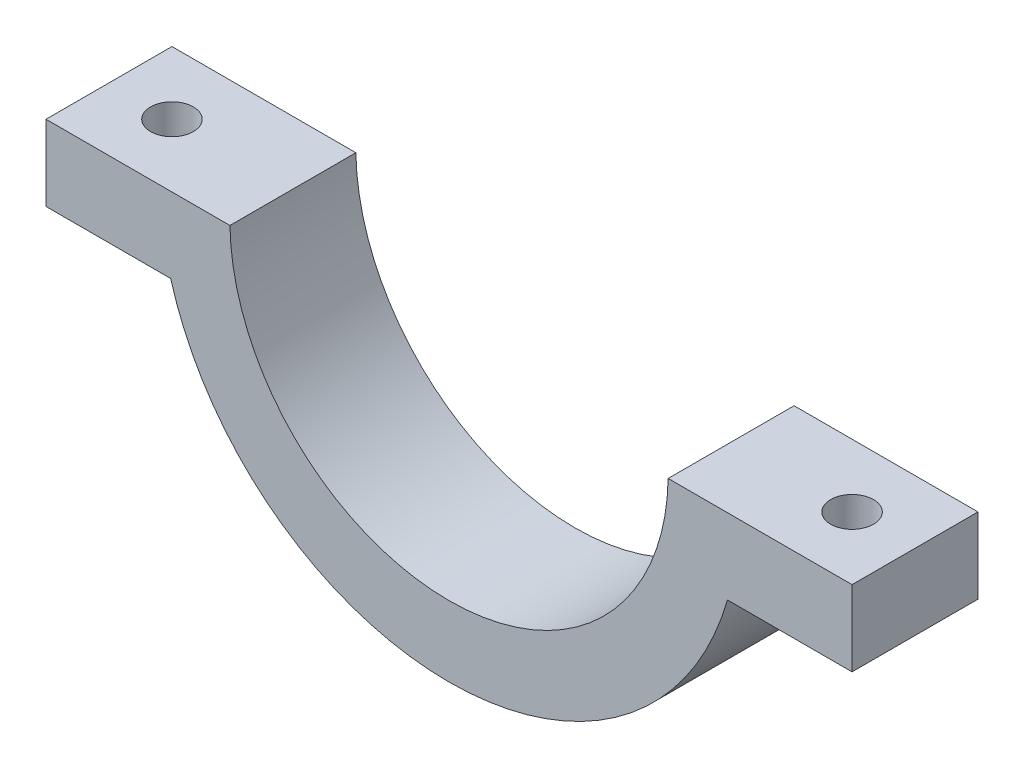
SolidWorks part; units mm, degrees
ref_plane "Front Plane" through (0, 0, 0) normal (0, 0, 1) x (1, 0, 0)
ref_plane "Top Plane" through (0, 0, 0) normal (0, 1, 0) x (1, 0, 0)
ref_plane "Right Plane" through (0, 0, 0) normal (1, 0, 0) x (0, 0, -1)
sketch "S01 - Rear semicircular cap and bolt ears" plane through (0, 0, 0) normal (0, 0, 1) x (1, 0, 0)
  line L0 (-32, -0.3) -> (-32, -6.3)
  line L1 (-32, -6.3) -> (-22.1, -6.3)
  line L2 (22.1, -6.3) -> (32, -6.3)
  line L3 (32, -6.3) -> (32, -0.3)
  line L4 (32, -0.3) -> (-32, -0.3)
  arc A0 (-22.1, -6.3) -> (22.1, -6.3) centre (0, -0.0269) ccw
  dimension "D1" = 22.9731
  dimension "D2" = 22.1
  dimension "D3" = 32
  dimension "D4" = 0.0269
  dimension "D5" = 32
  dimension "D6" = 0.3
extrude "01 - Rear semicircular cap and bolt ears" add sketch "S01 - Rear semicircular cap and bolt ears" along normal blind 10
sketch "S02 - Mating motor can" plane through (0, 0, 0) normal (0, 0, 1) x (1, 0, 0)
  circle A0 centre (0, 0) radius 17.4
  dimension "D1" = 34.8
extrude "02 - Mating motor can" cut sketch "S02 - Mating motor can" along normal blind 10.4 from offset 0.2 offset against normal yes
sketch3d "Plane points - Two M3 clamp screws"
  point P0 (0, 0, 0)
  point P1 (18, 0, 0)
  point P2 (0, 0, -18)
ref_plane "Drilling plane - Two M3 clamp screws" through (0, 0, 0) normal (0, 1, 0) x (1, 0, 0)
sketch "S03 - Two M3 clamp screws" plane through (0, 0, 0) normal (0, 1, 0) x (1, 0, 0)
  circle A0 centre (-27, -5) radius 1.7
  circle A1 centre (27, -5) radius 1.7
  dimension "D1" = 3.4
  dimension "D2" = 3.4
  dimension "D3" = 27
  dimension "D4" = 27
  dimension "D5" = 5
extrude "03 - Two M3 clamp screws" cut sketch "S03 - Two M3 clamp screws" along normal blind 6.7 from offset 6.5
